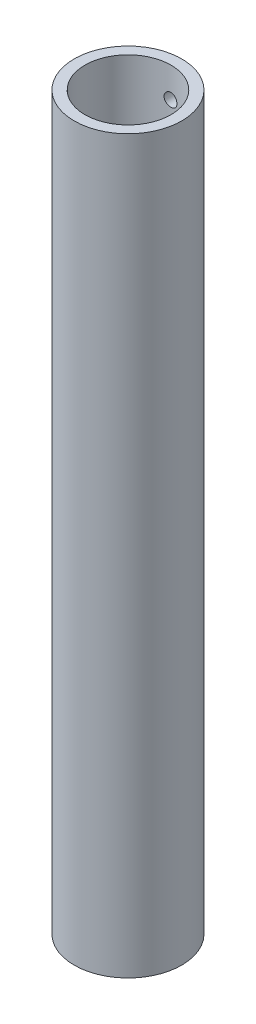
SolidWorks part; units mm, degrees
material "AISI 316 Annealed Stainless Steel Bar (SS)"
ref_plane "Front Plane" through (0, 0, 0) normal (0, 0, 1) x (1, 0, 0)
ref_plane "Top Plane" through (0, 0, 0) normal (0, 1, 0) x (1, 0, 0)
ref_plane "Right Plane" through (0, 0, 0) normal (1, 0, 0) x (0, 0, -1)
sketch "Sketch1" plane through (0, 0, 0) normal (0, 1, 0) x (1, 0, 0)
  circle A1 centre (0, 0) radius 12.5
  circle A2 centre (0, 0) radius 10
  dimension "D1" = 25
  dimension "D2" = 20
extrude "Boss-Extrude1" add sketch "Sketch1" along normal blind 170
ref_plane "Plane1" through (0, 0, -12.5) normal (0, 0, -1) x (-1, 0, 0)
sketch "Sketch2" plane through (0, 0, -12.5) normal (0, 0, -1) x (-1, 0, 0)
  line L0 (0, 0) -> (0, 178.5305) construction
  circle A0 centre (0, 163) radius 1.5
  point P2 (0, 0)
  dimension "D2" = 3
  dimension "D1" = 163
extrude "Cut-Extrude1" cut sketch "Sketch2" against normal blind 10
